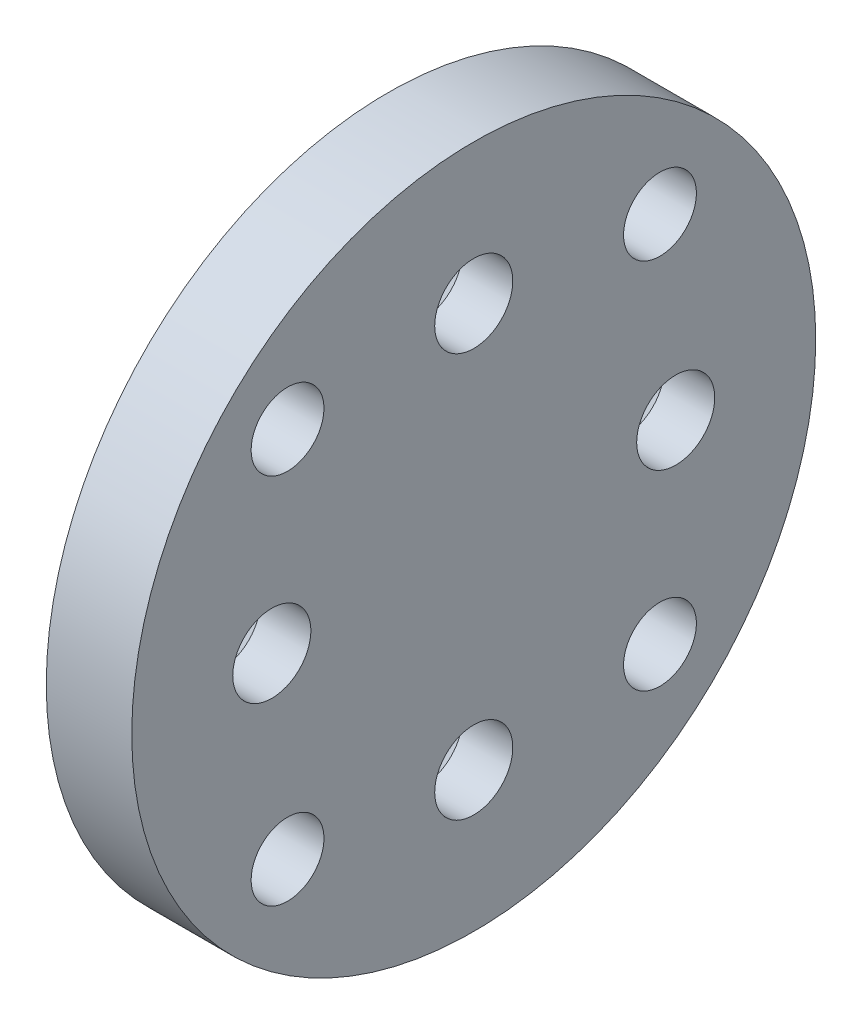
SolidWorks part; units mm, degrees
ref_plane "Front Plane" through (0, 0, 0) normal (0, 0, 1) x (1, 0, 0)
ref_plane "Top Plane" through (0, 0, 0) normal (0, 1, 0) x (1, 0, 0)
ref_plane "Right Plane" through (0, 0, 0) normal (1, 0, 0) x (0, 0, -1)
sketch "Sketch1" plane through (0, 0, 0) normal (1, 0, 0) x (0, 0, -1)
  circle A0 centre (0, 0) radius 12.7
  dimension "D1" = 25.4
extrude "Boss-Extrude1" add sketch "Sketch1" along normal blind 3.175
hole_wizard "CSK for M2.5 Flat Head Machine Screw1" positions "Sketch3" profile "Sketch2" countersink size "M2.5" standard "ANSI Metric" end condition through all
sketch "Sketch3" plane through (0, 0, 0) normal (-1, 0, 0) x (0, 0, 1)
  line L0 (-7.5, 0) -> (7.5, 0) construction
  line L3 (0, 7.5) -> (0, -7.5) construction
  point P0 (0, 7.5)
  point P2 (0, -7.5)
  point P4 (7.5, 0)
  point P6 (-7.5, 0)
  dimension "D1" = 15
sketch "Sketch2" plane through (0, 7.5, 0) normal (0, 1, 0) x (0, 0, 1)
  line L0 (0, 0) -> (0, 3.175)
  line L1 (0, 3.175) -> (1.45, 3.175)
  line L2 (1.45, 3.175) -> (1.45, 1.3)
  line L3 (1.45, 1.3) -> (2.75, 0)
  line L5 (2.75, 0) -> (0, 0)
  line L6 (-1.45, 1.3) -> (-2.75, 0) construction
  line L11 (0, -6.35) -> (0, 107.95) construction
  dimension "Thru Hole Dia." = 2.9
  dimension "Thru Hole Depth" = 3.175
  dimension "Near C'Sink Dia." = 5.5
  dimension "Near C'Sink Angle" = 90
hole_wizard "#6-32 Tapped Hole1" positions "Sketch5" profile "Sketch4" tap size "#6-32" standard "ANSI Inch" end condition through all
sketch "Sketch5" plane through (0, 0, 0) normal (-1, 0, 0) x (0, 0, 1)
  line L0 (-6.9148, 6.9148) -> (6.9148, -6.9148) construction
  line L3 (6.9148, 6.9148) -> (-6.9148, -6.9148) construction
  point P0 (-6.9148, 6.9148)
  point P2 (-6.9148, -6.9148)
  point P4 (6.9148, 6.9148)
  point P6 (6.9148, -6.9148)
  dimension "D1" = 19.558
sketch "Sketch4" plane through (0, 6.9148, -6.9148) normal (0, 1, 0) x (0, 0, 1)
  line L0 (0, 0) -> (0, 3.175)
  line L1 (0, 3.175) -> (1.3525, 3.175)
  line L2 (1.3525, 3.175) -> (1.3525, 0)
  line L5 (1.3525, 0) -> (0, 0)
  line L11 (0, -6.35) -> (0, 107.95) construction
  dimension "Thread Major Dia." = 2.7051
  dimension "Thru Tap Drill Depth" = 3.175
